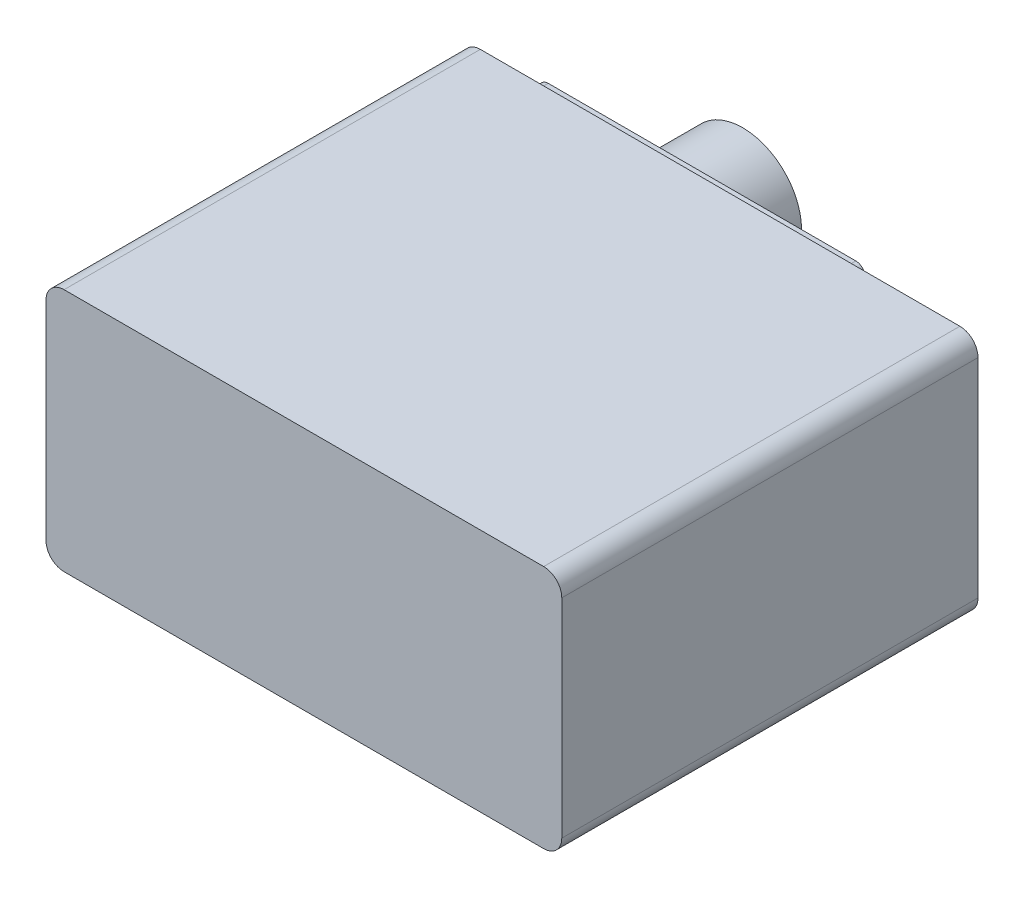
SolidWorks part; units mm, degrees
ref_plane "Plan de face" through (0, 0, 0) normal (0, 0, 1) x (1, 0, 0)
ref_plane "Plan de dessus" through (0, 0, 0) normal (0, 1, 0) x (1, 0, 0)
ref_plane "Plan de droite" through (0, 0, 0) normal (1, 0, 0) x (0, 0, -1)
sketch "Esquisse1" plane through (0, 0, 0) normal (0, 0, 1) x (1, 0, 0)
  line L0 (0, 0) -> (0, -13.5) construction
  line L1 (0, -13.5) -> (28.5, -13.5)
  line L2 (28.5, -13.5) -> (28.5, 13.5)
  line L3 (28.5, 13.5) -> (-28.5, 13.5)
  line L4 (-28.5, 13.5) -> (-28.5, -13.5)
  line L5 (-28.5, -13.5) -> (0, -13.5)
  dimension "D1" = 27
  dimension "D2" = 28.5
  dimension "D3" = 57
extrude "Boss.-Extru.1" add sketch "Esquisse1" along normal blind 46
fillet "Congé1" radius 2 4 edges at (-28.5, 13.5, 23) (28.5, 13.5, 23) (28.5, -13.5, 23) (-28.5, -13.5, 23)
sketch "Esquisse2" plane through (0, 0, 0) normal (0, 0, -1) x (-1, 0, 0)
  line L0 (0, 0) -> (24, 0) construction
  line L1 (0, 0) -> (-12, 0) construction
  line L2 (-12, 0) -> (-12, 10) construction
  line L4 (24, 10) -> (24, -10)
  line L5 (24, -10) -> (-12, -10)
  line L6 (-12, -10) -> (-12, 10)
  line L7 (-12, 10) -> (24, 10)
  dimension "D2" = 20
  dimension "D3" = 24
extrude "Boss.-Extru.2" add sketch "Esquisse2" along normal blind 4
fillet "Congé3" radius 1 4 edges at (12, 10, -2) (-24, 10, -2) (-24, -10, -2) (12, -10, -2)
sketch "Esquisse4" plane through (0, 0, -4) normal (0, 0, -1) x (-1, 0, 0)
  line L0 (-28.5, 0) -> (11.5, 0) construction
  line L1 (-28.5, -11.5) -> (-28.5, 11.5) construction
  circle A0 centre (11.5, 0) radius 6.5
extrude "Boss.-Extru.3" add sketch "Esquisse4" along normal blind 10
sketch "Esquisse5" plane through (0, 0, -14) normal (0, 0, -1) x (-1, 0, 0)
  line L0 (5, 0) -> (18, 0) construction
  circle A0 centre (11.5, 0) radius 6.5 construction
  circle A1 centre (11.5, 0) radius 6.5 construction
  circle A2 centre (11.5, 0) radius 3
  circle A3 centre (11.5, 0) radius 5
extrude "Enlèv. mat.-Extru.1" cut sketch "Esquisse5" against normal blind 2
sketch "Esquisse7" plane through (0, 0, 0) normal (0, 0, -1) x (-1, 0, 0)
  line L0 (-12, 0) -> (-12, 5) construction
  line L1 (-12, 9) -> (-12, -9) construction
  line L2 (-12, 0) -> (-12, -5)
  line L3 (-12, 9) -> (-12, -9) construction
  line L4 (-12, 0) -> (-12, 5)
  arc A0 (-12, 5) -> (-12, -5) centre (-12, 0) ccw
  line M16 (-12, -9) -> (-12, 9)
extrude "Boss.-Extru.4" add sketch "Esquisse7" along normal blind 4 contours A0 M16
